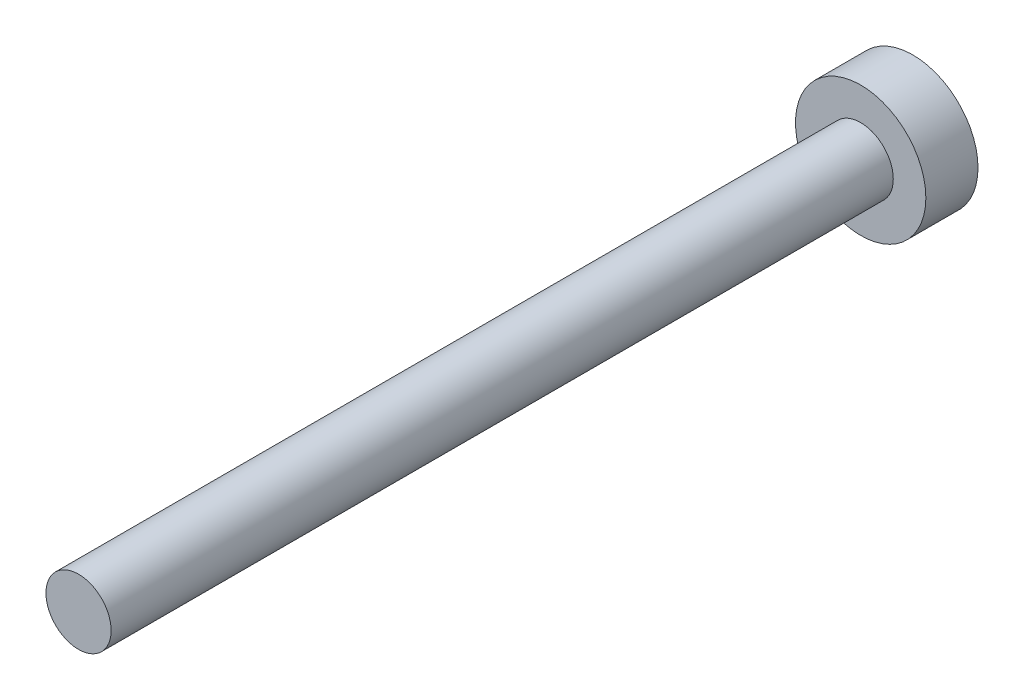
SolidWorks part; units mm, degrees
material "AISI 304"
ref_plane "Front" through (0, 0, 0) normal (0, 0, 1) x (1, 0, 0)
ref_plane "Top" through (0, 0, 0) normal (0, 1, 0) x (1, 0, 0)
ref_plane "Right" through (0, 0, 0) normal (1, 0, 0) x (0, 0, -1)
sketch "Sketch1" plane through (0, 0, 0) normal (0, 0, 1) x (1, 0, 0)
  circle A0 centre (0, 0) radius 7.9375
  dimension "D1" = 15.875
extrude "Boss-Extrude1" add sketch "Sketch1" along normal blind 6.35
sketch "Sketch2" plane through (0, 0, 6.35) normal (0, 0, 1) x (1, 0, 0)
  circle A0 centre (0, 0) radius 3.9688
  dimension "D1" = 7.9375
extrude "Boss-Extrude2" add sketch "Sketch2" along normal blind 95.25
